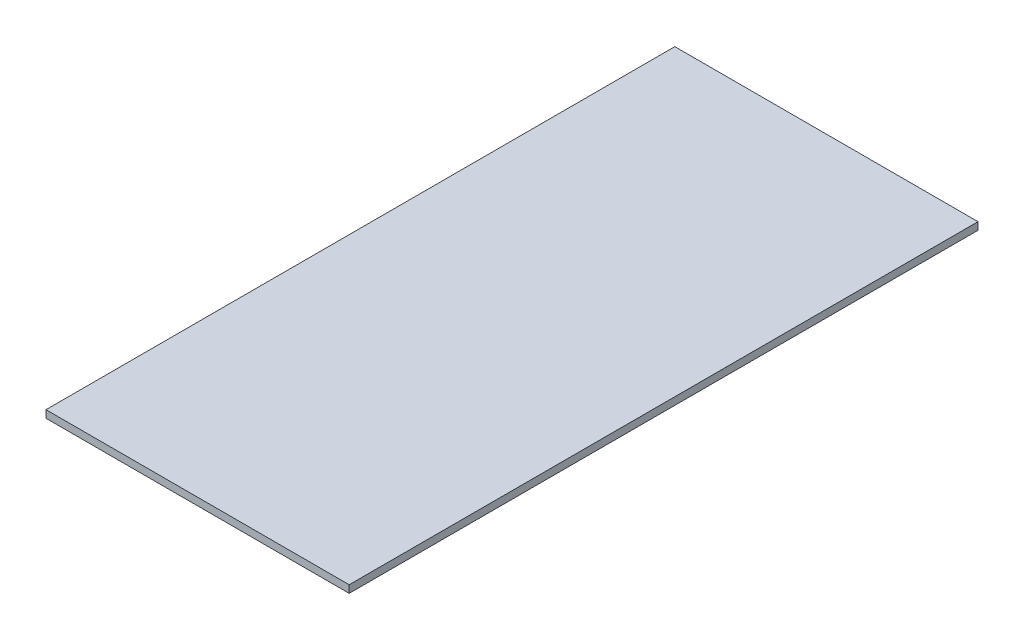
SolidWorks part; units mm, degrees
material "Pine"
ref_plane "Front Plane" through (0, 0, 0) normal (0, 0, 1) x (1, 0, 0)
ref_plane "Top Plane" through (0, 0, 0) normal (0, 1, 0) x (1, 0, 0)
ref_plane "Right Plane" through (0, 0, 0) normal (1, 0, 0) x (0, 0, -1)
sketch "Sketch1" plane through (0, 0, 0) normal (0, 1, 0) x (1, 0, 0)
  line L1 (-257.175, -533.4) -> (257.175, -533.4)
  line L2 (-257.175, -533.4) -> (-257.175, 533.4)
  line L3 (-257.175, 533.4) -> (257.175, 533.4)
  line L4 (257.175, -533.4) -> (257.175, 533.4)
  line L5 (-257.175, -533.4) -> (257.175, 533.4) construction
  line L6 (-257.175, 533.4) -> (257.175, -533.4) construction
  point P0 (0, 0)
  dimension "D1" = 514.35
  dimension "D2" = 1066.8
extrude "Boss-Extrude1" add sketch "Sketch1" along normal blind 12.7
